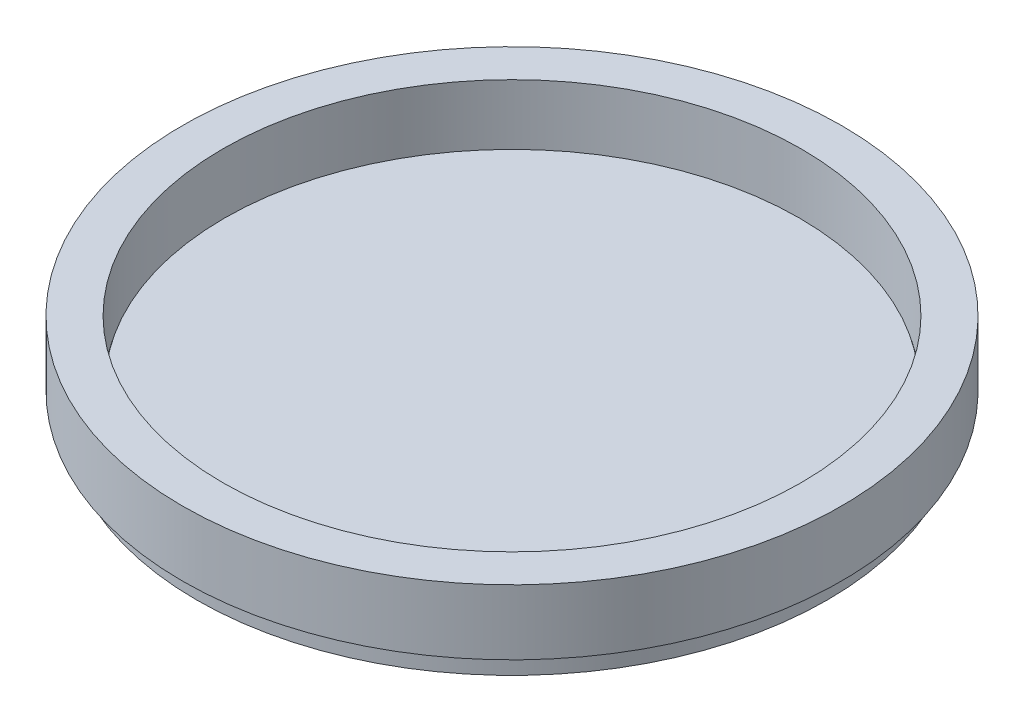
SolidWorks part; units mm, degrees
ref_plane "Спереди" through (0, 0, 0) normal (0, 0, 1) x (1, 0, 0)
ref_plane "Сверху" through (0, 0, 0) normal (0, 1, 0) x (1, 0, 0)
ref_plane "Справа" through (0, 0, 0) normal (1, 0, 0) x (0, 0, -1)
other "Configuration Table"
sketch "Эскиз1" plane through (0, 0, 0) normal (0, 1, 0) x (1, 0, 0)
  circle A0 centre (0, 0) radius 28.65
  circle A1 centre (0, 0) radius 25.14
  dimension "D1" = 3.51
  dimension "D2" = 57.3
extrude "Бобышка-Вытянуть1" add sketch "Эскиз1" along normal blind 5.65
sketch "Эскиз2" plane through (0, 0, 0) normal (0, -1, 0) x (1, 0, 0)
  circle A0 centre (0, 0) radius 24.94
  circle A1 centre (0, 0) radius 27.42
  dimension "D1" = 2.48
  dimension "D2" = 49.88
extrude "Бобышка-Вытянуть2" add sketch "Эскиз2" along normal blind 2.04
cosmetic thread "Условное изображение резьбы1" parameters "D2"=42.516
sketch "Эскиз3" plane through (0, 0, 0) normal (0, 1, 0) x (1, 0, 0)
  circle A0 centre (0, 0) radius 25
  dimension "D1" = 50
extrude "Бобышка-Вытянуть3" add sketch "Эскиз3" along normal mid plane 1
